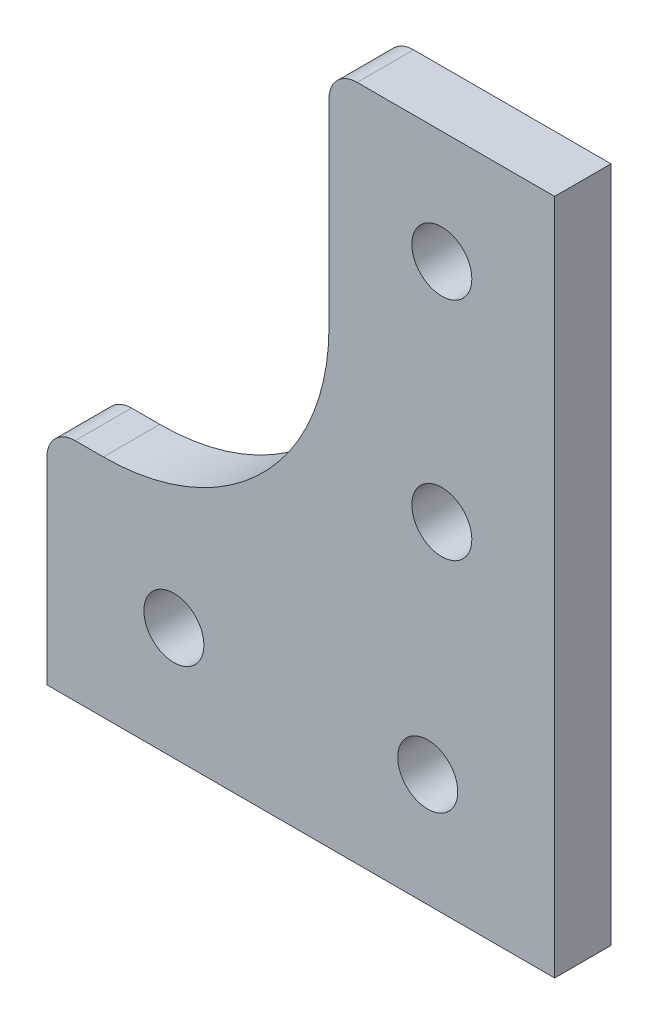
SolidWorks part; units mm, degrees
ref_plane "Front Plane" through (0, 0, 0) normal (0, 0, 1) x (1, 0, 0)
ref_plane "Top Plane" through (0, 0, 0) normal (0, 1, 0) x (1, 0, 0)
ref_plane "Right Plane" through (0, 0, 0) normal (1, 0, 0) x (0, 0, -1)
sketch "Sketch1" plane through (0, 0, 0) normal (0, 0, 1) x (1, 0, 0)
  line L0 (-28.575, -12.7) -> (28.575, -12.7)
  line L1 (28.575, -12.7) -> (28.575, 63.5)
  line L2 (28.575, 63.5) -> (3.175, 63.5)
  line L3 (3.175, 63.5) -> (3.175, 12.7)
  line L4 (3.175, 12.7) -> (-28.575, 12.7)
  line L5 (-28.575, 12.7) -> (-28.575, -12.7)
  point P6 (0, -12.7)
  point P7 (-28.575, 0)
  dimension "D1" = 25.4
  dimension "D2" = 25.4
  dimension "D3" = 50.8
  dimension "D4" = 28.575
extrude "Boss-Extrude1" add sketch "Sketch1" along normal mid plane 6.35
sketch "Sketch2" plane through (0, 0, 3.175) normal (0, 0, 1) x (1, 0, 0)
  circle A0 centre (15.875, 25.4) radius 3.3782 construction
  circle A1 centre (15.875, 50.8) radius 3.3782 construction
  circle A2 centre (15.875, 25.4) radius 3.3782
  circle A3 centre (15.875, 50.8) radius 3.3782
extrude "Cut-Extrude1" cut sketch "Sketch2" against normal through all
sketch "Sketch3" plane through (0, 0, 3.175) normal (0, 0, 1) x (1, 0, 0)
  line L0 (-14.2875, 0) -> (14.2875, 0) construction
  circle A0 centre (-14.2875, 0) radius 3.3782
  circle A1 centre (14.2875, 0) radius 3.3782
  point P5 (0, 0)
  dimension "D1" = 6.7564
  dimension "D2" = 6.7564
  dimension "D3" = 28.575
extrude "Cut-Extrude2" cut sketch "Sketch3" against normal through all contours A0
fillet "Fillet1" radius 25.4 1 edges at (3.175, 12.7, 0)
fillet "Fillet2" radius 3.175 2 edges at (-28.575, 12.7, 0) (3.175, 63.5, 0)
